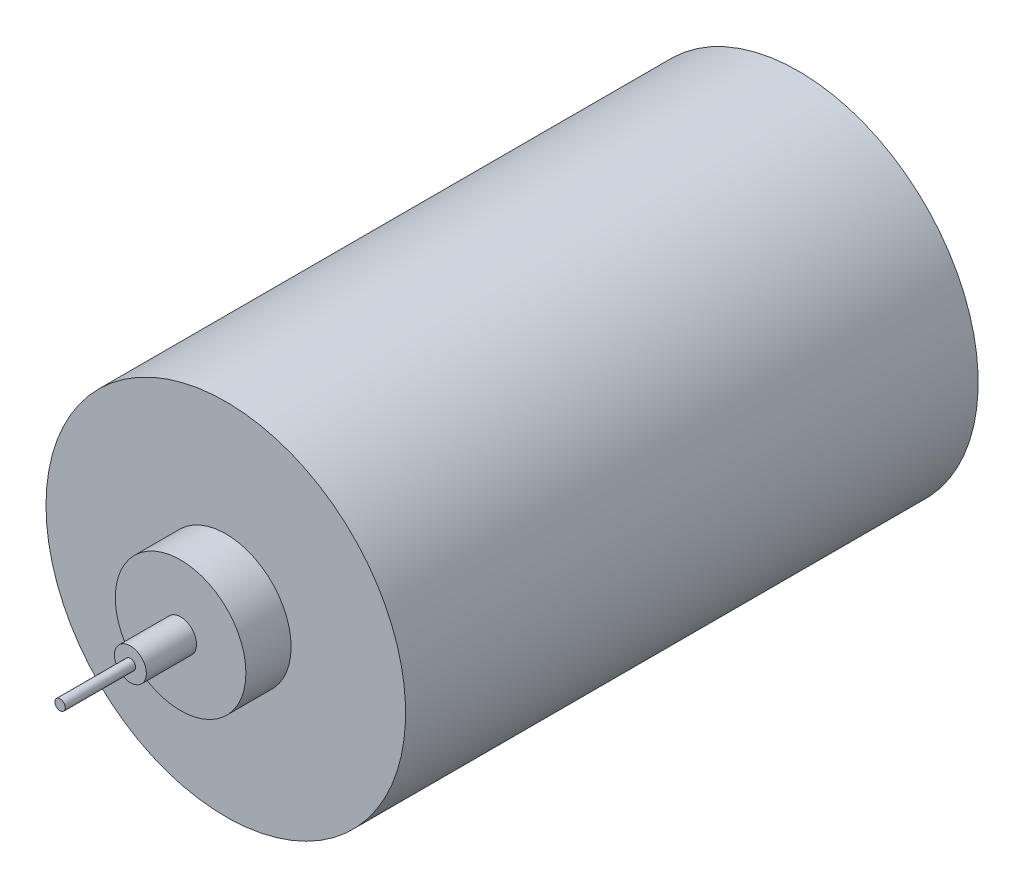
SolidWorks part; units mm, degrees
ref_plane "Front Plane" through (0, 0, 0) normal (0, 0, 1) x (1, 0, 0)
ref_plane "Top Plane" through (0, 0, 0) normal (0, 1, 0) x (1, 0, 0)
ref_plane "Right Plane" through (0, 0, 0) normal (1, 0, 0) x (0, 0, -1)
sketch "Sketch1" plane through (0, 0, 0) normal (0, 0, 1) x (1, 0, 0)
  circle A0 centre (0, 0) radius 17.9
  dimension "D1" = 35.8
extrude "Boss-Extrude1" add sketch "Sketch1" along normal blind 57
sketch "Sketch2" plane through (0, 0, 57) normal (0, 0, 1) x (1, 0, 0)
  circle A0 centre (0, 0) radius 6.5
  dimension "D1" = 13
extrude "Boss-Extrude2" add sketch "Sketch2" along normal blind 4.5
sketch "Sketch3" plane through (0, 0, 61.5) normal (0, 0, 1) x (1, 0, 0)
  circle A0 centre (0, 0) radius 1.5875
  dimension "D1" = 3.175
extrude "Boss-Extrude3" add sketch "Sketch3" along normal blind 12
sketch "Sketch4" plane through (0, 0, 73.5) normal (0, 0, 1) x (1, 0, 0)
  circle A0 centre (0, 0) radius 0.5189
  circle A1 centre (0, 0) radius 1.5875
extrude "Cut-Extrude1" cut sketch "Sketch4" against normal blind 7
